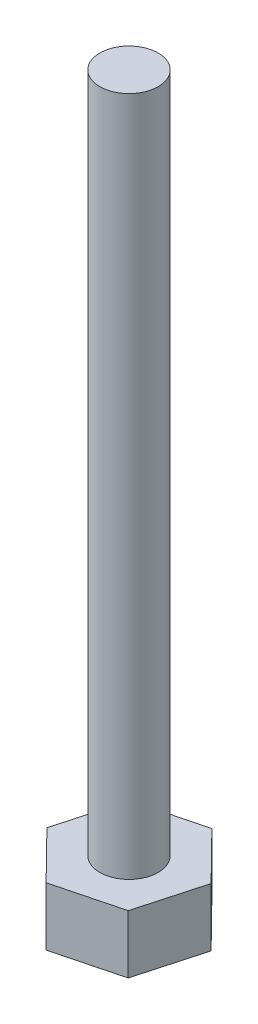
SolidWorks part; units mm, degrees
ref_plane "Plan de face" through (0, 0, 0) normal (0, 0, 1) x (1, 0, 0)
ref_plane "Plan de dessus" through (0, 0, 0) normal (0, 1, 0) x (1, 0, 0)
ref_plane "Plan de droite" through (0, 0, 0) normal (1, 0, 0) x (0, 0, -1)
ref_plane "Plan1" through (0, -38, 0) normal (0, -1, 0) x (1, 0, 0)
sketch "Esquisse1" plane through (0, -38, 0) normal (0, -1, 0) x (1, 0, 0)
  line L0 (0.9242, -3.3385) -> (3.3534, -0.8689)
  line L1 (3.3534, -0.8689) -> (2.4292, 2.4696)
  line L2 (2.4292, 2.4696) -> (-0.9242, 3.3385)
  line L3 (-0.9242, 3.3385) -> (-3.3534, 0.8689)
  line L4 (-3.3534, 0.8689) -> (-2.4292, -2.4696)
  line L5 (-2.4292, -2.4696) -> (0.9242, -3.3385)
extrude "Boss.-Extru.1" add sketch "Esquisse1" against normal blind 3
ref_plane "Plan2" through (0, 0, 0) normal (0, 0, -1) x (-1, 0, 0)
sketch "Esquisse2" plane through (0, 0, 0) normal (0, 0, -1) x (-1, 0, 0)
  line L0 (-1.5, -35) -> (0, -35)
  line L1 (0, -35) -> (0, 0)
  line L2 (0, 0) -> (-1.5, 0)
  line L3 (-1.5, 0) -> (-1.5, -35)
  line L4 (0, -35) -> (0, 0) construction
revolve "Révolution1" add sketch "Esquisse2" angle 360 about L4
